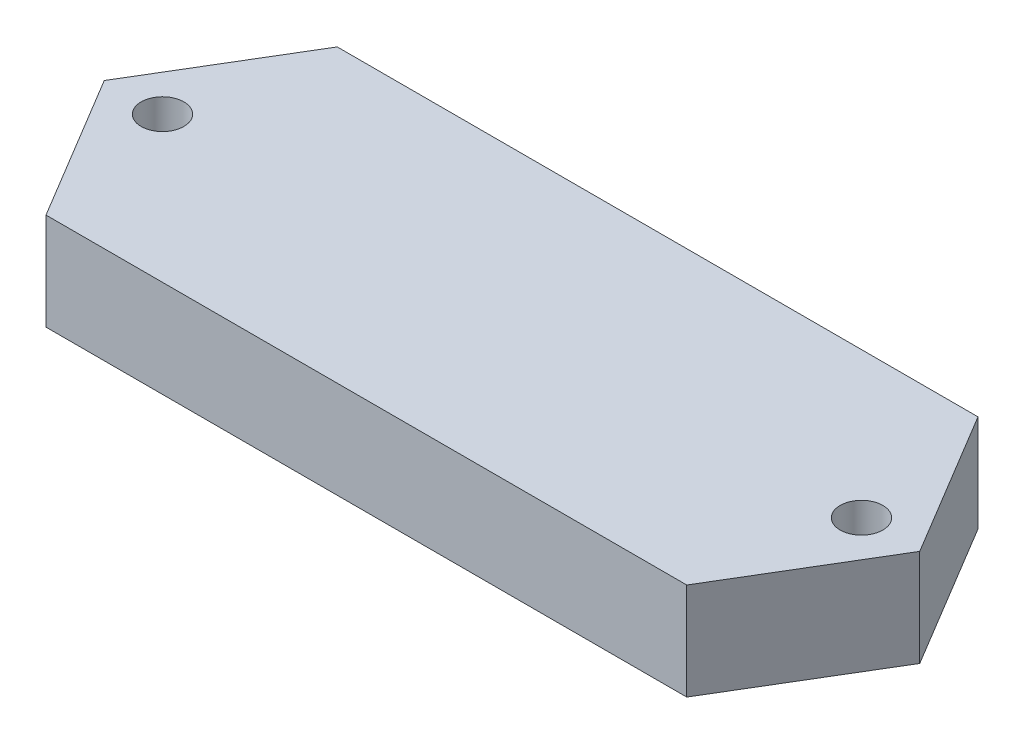
SolidWorks part; units mm, degrees
ref_plane "前视基准面" through (0, 0, 0) normal (0, 0, 1) x (1, 0, 0)
ref_plane "上视基准面" through (0, 0, 0) normal (0, 1, 0) x (1, 0, 0)
ref_plane "右视基准面" through (0, 0, 0) normal (1, 0, 0) x (0, 0, -1)
other "Configuration Table"
sketch "草图1" plane through (0, 0, 0) normal (0, 1, 0) x (1, 0, 0)
  line L0 (-16.5, -7.5) -> (-21, 0)
  line L1 (16.5, 7.5) -> (-16.5, 7.5)
  line L2 (16.5, 7.5) -> (16.5, -7.5)
  line L3 (16.5, -7.5) -> (-16.5, -7.5)
  line L4 (-16.5, 7.5) -> (-16.5, -7.5)
  line L5 (16.5, 7.5) -> (-16.5, -7.5) construction
  line L6 (16.5, -7.5) -> (-16.5, 7.5) construction
  line L7 (-21, 0) -> (-16.5, 7.5)
  line L8 (-16.5, 0) -> (16.5, 0) construction
  line L9 (0, 7.5) -> (0, -7.5) construction
  line L10 (21, 0) -> (16.5, 7.5)
  line L11 (16.5, -7.5) -> (21, 0)
  circle A0 centre (-18, 0) radius 1.1
  circle A1 centre (18, 0) radius 1.1
  point P0 (0, 0)
  point P13 (0, 0)
  dimension "D4" = 2.2
  dimension "D1" = 33
  dimension "D2" = 15
  dimension "D3" = 21
  dimension "D5" = 36
extrude "凸台-拉伸1" add sketch "草图1" along normal blind 5 contours L1 L4 L3 L2 | L7 L0 L4 A0 | L2 L11 L10 A1
